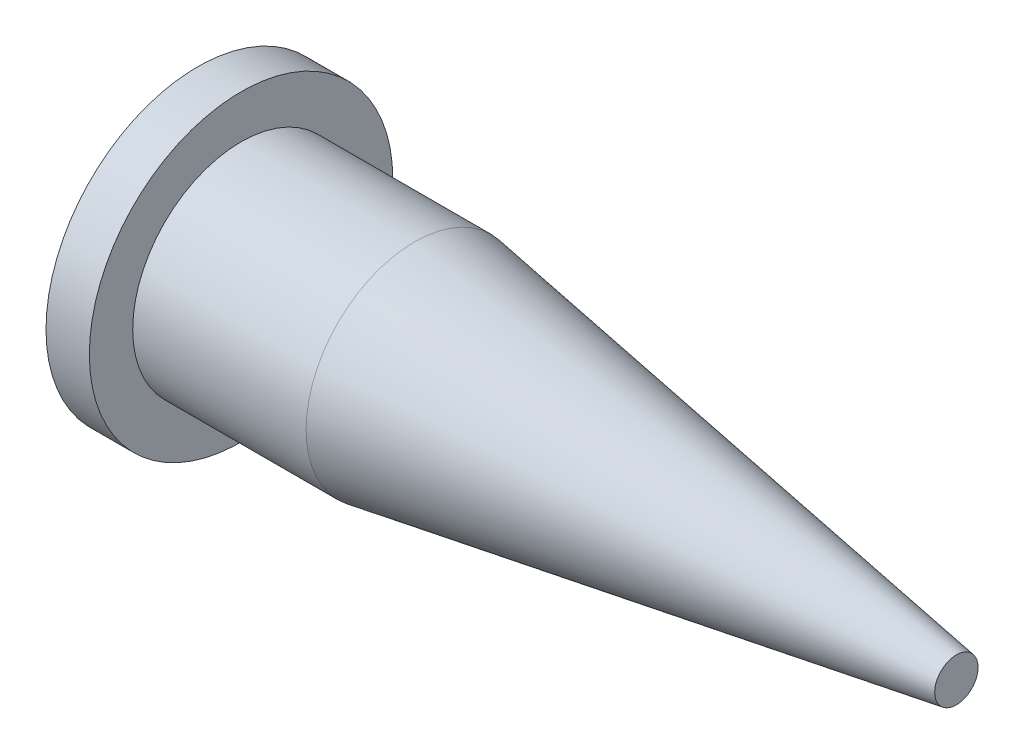
SolidWorks part; units mm, degrees
ref_plane "Piano frontale" through (0, 0, 0) normal (0, 0, 1) x (1, 0, 0)
ref_plane "Piano superiore" through (0, 0, 0) normal (0, 1, 0) x (1, 0, 0)
ref_plane "Piano destro" through (0, 0, 0) normal (1, 0, 0) x (0, 0, -1)
sketch "Schizzo1" plane through (0, 0, 0) normal (0, 1, 0) x (1, 0, 0)
  line L0 (-8.8785, 4.8131) -> (-8.8785, 2.8131)
  line L2 (-10.8785, 4.8131) -> (-10.8785, -2.1869)
  line L3 (-10.8785, -2.1869) -> (24.1215, -2.1869)
  line L5 (-8.8785, 2.8131) -> (-0.8785, 2.8131)
  line L6 (-0.8785, 2.8131) -> (24.1215, -1.1869)
  line L7 (-10.8785, 4.8131) -> (-8.8785, 4.8131)
  line L8 (24.1215, -1.1869) -> (24.1215, -2.1869)
  line L9 (-0.8785, -2.1869) -> (-0.8785, 2.8131) construction
  dimension "D1" = 2
  dimension "D2" = 7
  dimension "D3" = 8
  dimension "D4" = 1
  dimension "D5" = 5
  dimension "D6" = 25
  dimension "D7" = 2.1869
  dimension "D8" = 10.8785
revolve "Rivoluzione1" add sketch "Schizzo1" angle 360 about L3
